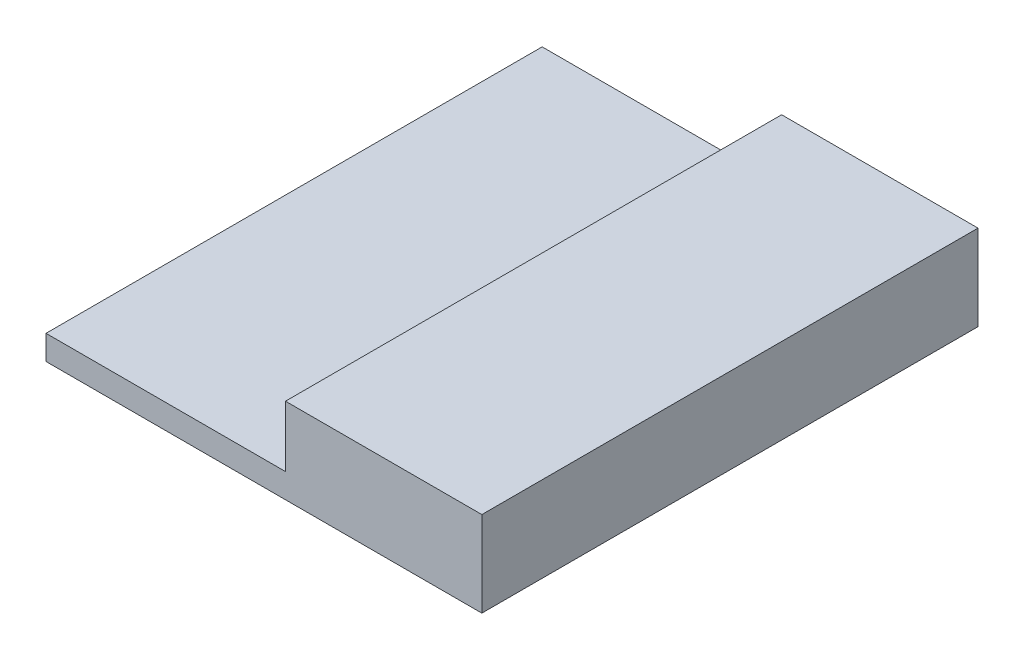
SolidWorks part; units mm, degrees
ref_plane "Front Plane" through (0, 0, 0) normal (0, 0, 1) x (1, 0, 0)
ref_plane "Top Plane" through (0, 0, 0) normal (0, 1, 0) x (1, 0, 0)
ref_plane "Right Plane" through (0, 0, 0) normal (1, 0, 0) x (0, 0, -1)
sketch "Sketch1" plane through (0, 0, 0) normal (0, 1, 0) x (1, 0, 0)
  line L1 (0, 0) -> (94.2941, 0)
  line L2 (0, 0) -> (0, 123.2475)
  line L3 (0, 123.2475) -> (94.2941, 123.2475)
  line L4 (94.2941, 0) -> (94.2941, 123.2475)
extrude "Boss-Extrude1" add sketch "Sketch1" along normal blind 41
sketch "Sketch2" plane through (0, 0, 0) normal (-1, 0, 0) x (0, 0, 1)
  line L0 (0, 41) -> (0, 0) construction
  line L1 (-123.2475, 0) -> (0, 0)
  line L2 (-123.2475, 0) -> (-123.2475, 11.7295)
  line L3 (-123.2475, 11.7295) -> (0, 11.7295)
  line L4 (0, 0) -> (0, 11.7295)
extrude "Boss-Extrude2" add sketch "Sketch2" along normal blind 115
sketch "Sketch3" plane through (0, 0, -123.2475) normal (0, 0, -1) x (-1, 0, 0)
  line L1 (-94.2941, 0) -> (0, 0)
  line L2 (-94.2941, 0) -> (-94.2941, 41)
  line L3 (-94.2941, 41) -> (0, 41)
  line L4 (0, 0) -> (0, 41)
  line L5 (0, 0) -> (115, 0)
  line L6 (0, 0) -> (0, 11.7295)
  line L7 (0, 11.7295) -> (115, 11.7295)
  line L8 (115, 0) -> (115, 11.7295)
  line M1 (-94.2941, 0) -> (115, 0)
  line M2 (115, 0) -> (115, 11.7295)
  line M3 (115, 11.7295) -> (0, 11.7295)
  line M4 (0, 11.7295) -> (0, 41)
  line M5 (0, 41) -> (-94.2941, 41)
  line M6 (-94.2941, 41) -> (-94.2941, 0)
extrude "Boss-Extrude3" add sketch "Sketch3" along normal blind 115 contours L4 M1 M4 M5 M6 | L4 M1 M2 M3
